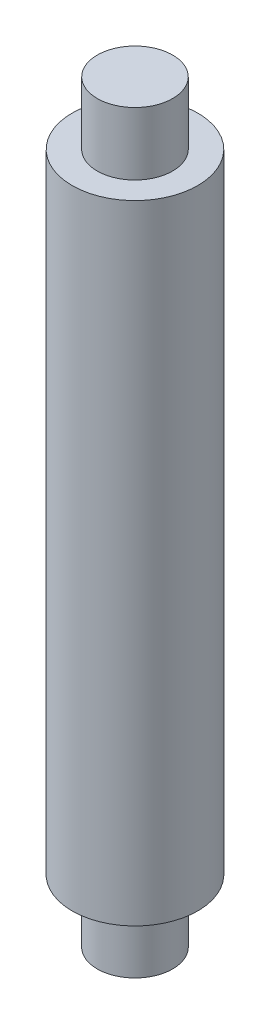
SolidWorks part; units mm, degrees
ref_plane "Alzado" through (0, 0, 0) normal (0, 0, 1) x (1, 0, 0)
ref_plane "Planta" through (0, 0, 0) normal (0, 1, 0) x (1, 0, 0)
ref_plane "Vista lateral" through (0, 0, 0) normal (1, 0, 0) x (0, 0, -1)
sketch "Croquis1" plane through (0, 0, 0) normal (0, 0, 1) x (1, 0, 0)
  line L0 (0, 0) -> (-6, 0)
  line L1 (-6, 0) -> (-6, 10)
  line L2 (-6, 10) -> (-10, 10)
  line L3 (-10, 10) -> (-10, 110)
  line L4 (-10, 110) -> (-6, 110)
  line L5 (-6, 110) -> (-6, 120)
  line L6 (-6, 120) -> (0, 120)
  line L7 (0, 120) -> (0, 0)
  dimension "D1" = 120
  dimension "D2" = 6
  dimension "D3" = 10
  dimension "D4" = 10
  dimension "D5" = 100
  dimension "D6" = 6
revolve "Revolución1" add sketch "Croquis1" angle 360 about L7
